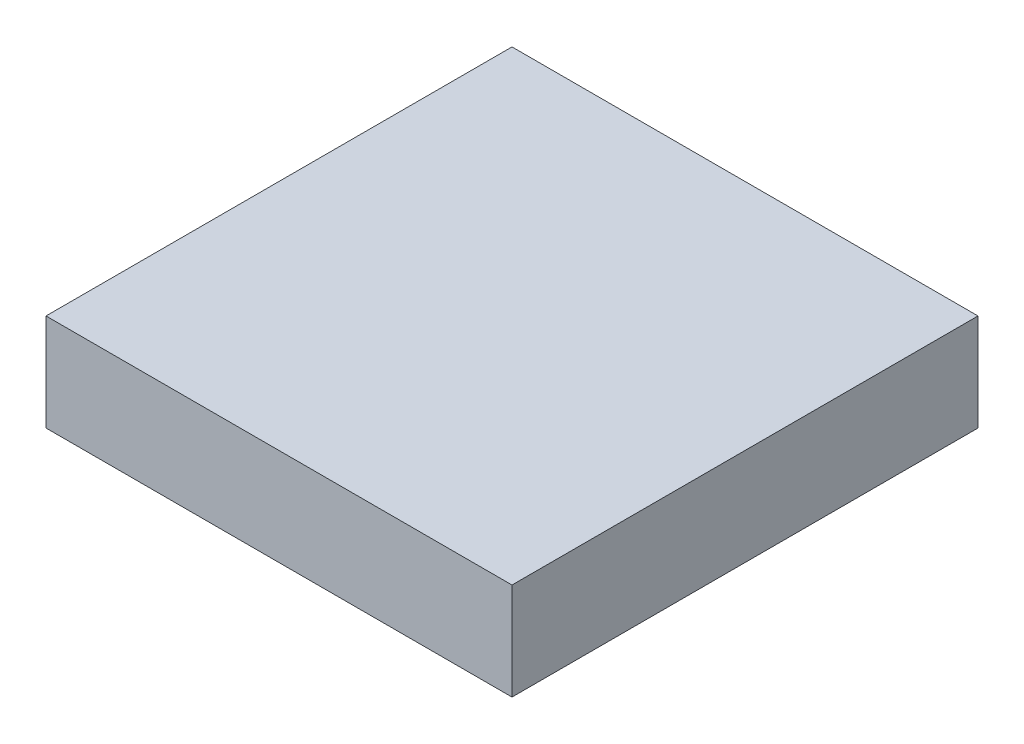
SolidWorks part; units mm, degrees
ref_plane "Front Plane" through (0, 0, 0) normal (0, 0, 1) x (1, 0, 0)
ref_plane "Top Plane" through (0, 0, 0) normal (0, 1, 0) x (1, 0, 0)
ref_plane "Right Plane" through (0, 0, 0) normal (1, 0, 0) x (0, 0, -1)
sketch "Sketch1" plane through (0, 0, 0) normal (0, 1, 0) x (1, 0, 0)
  line L0 (-60, -60) -> (-22.5933, -60)
  line L2 (-60, -60) -> (-60, 60)
  line L3 (-60, 60) -> (60, 60)
  line L4 (60, -60) -> (60, 60)
  line L5 (-60, -60) -> (60, 60) construction
  line L6 (-60, 60) -> (60, -60) construction
  line L10 (32.1773, -60) -> (60, -60)
  line L11 (-22.5933, -60) -> (32.1773, -60)
  point P0 (0, 0)
  dimension "D1" = 120
  dimension "D2" = 120
extrude "Boss-Extrude1" add sketch "Sketch1" along normal blind 25
